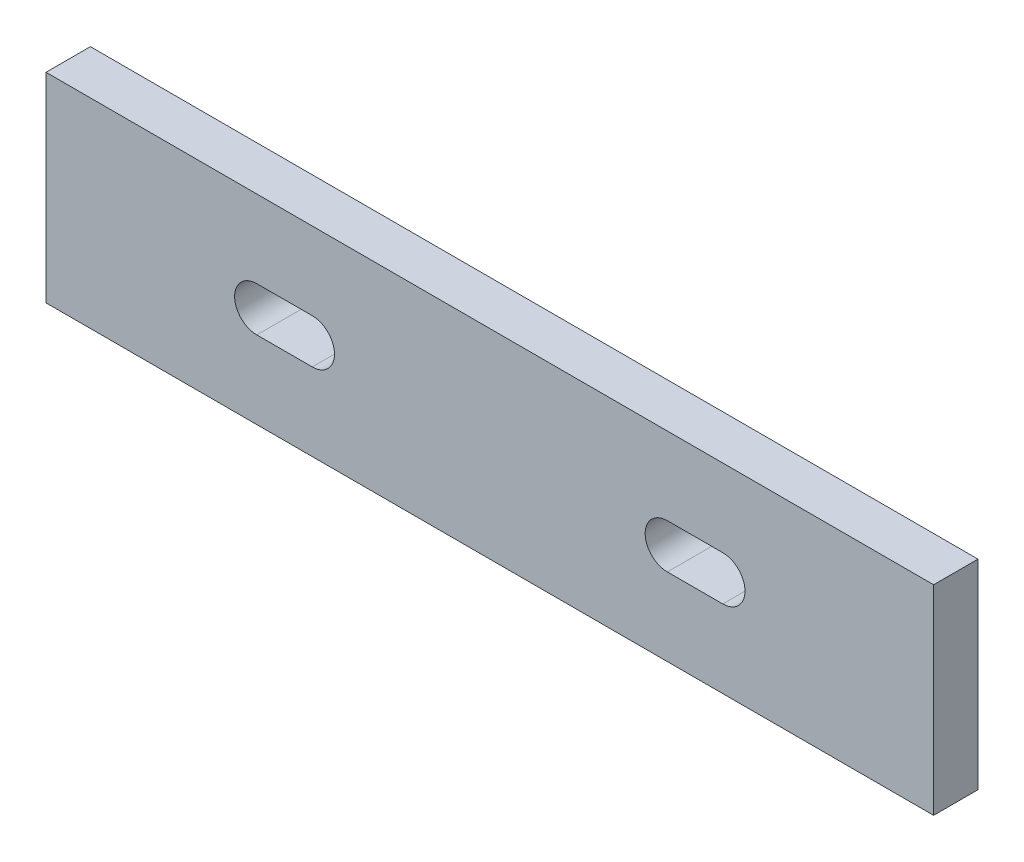
SolidWorks part; units mm, degrees
material "ASTM A36 Steel"
ref_plane "Front Plane" through (0, 0, 0) normal (0, 0, 1) x (1, 0, 0)
ref_plane "Top Plane" through (0, 0, 0) normal (0, 1, 0) x (1, 0, 0)
ref_plane "Right Plane" through (0, 0, 0) normal (1, 0, 0) x (0, 0, -1)
sketch "Sketch2" plane through (0, 0, 0) normal (0, 0, 1) x (1, 0, 0)
  line L0 (107.5083, -33.8779) -> (82.5083, -33.8779) construction
  line L1 (202.5083, 11.1221) -> (-197.4917, 11.1221)
  line L2 (202.5083, 11.1221) -> (202.5083, -78.8779)
  line L3 (202.5083, -78.8779) -> (-197.4917, -78.8779)
  line L4 (-197.4917, 11.1221) -> (-197.4917, -78.8779)
  line L5 (107.5083, -43.8779) -> (82.5083, -43.8779)
  line L6 (107.5083, -23.8779) -> (82.5083, -23.8779)
  line L7 (-77.4917, -33.8779) -> (-102.4917, -33.8779) construction
  line L8 (-77.4917, -43.8779) -> (-102.4917, -43.8779)
  line L9 (-77.4917, -23.8779) -> (-102.4917, -23.8779)
  arc A0 (107.5083, -43.8779) -> (107.5083, -23.8779) centre (107.5083, -33.8779) ccw
  arc A1 (82.5083, -23.8779) -> (82.5083, -43.8779) centre (82.5083, -33.8779) ccw
  arc A2 (-77.4917, -43.8779) -> (-77.4917, -23.8779) centre (-77.4917, -33.8779) ccw
  arc A3 (-102.4917, -23.8779) -> (-102.4917, -43.8779) centre (-102.4917, -33.8779) ccw
  point P6 (95.0083, -33.8779)
  point P11 (-89.9917, -33.8779)
  dimension "D1" = 400
  dimension "D2" = 90
  dimension "D3" = 25
  dimension "D4" = 25
  dimension "D5" = 20
  dimension "D6" = 20
  dimension "D7" = 95
  dimension "D8" = 185
extrude "Boss-Extrude1" add sketch "Sketch2" along normal blind 20
